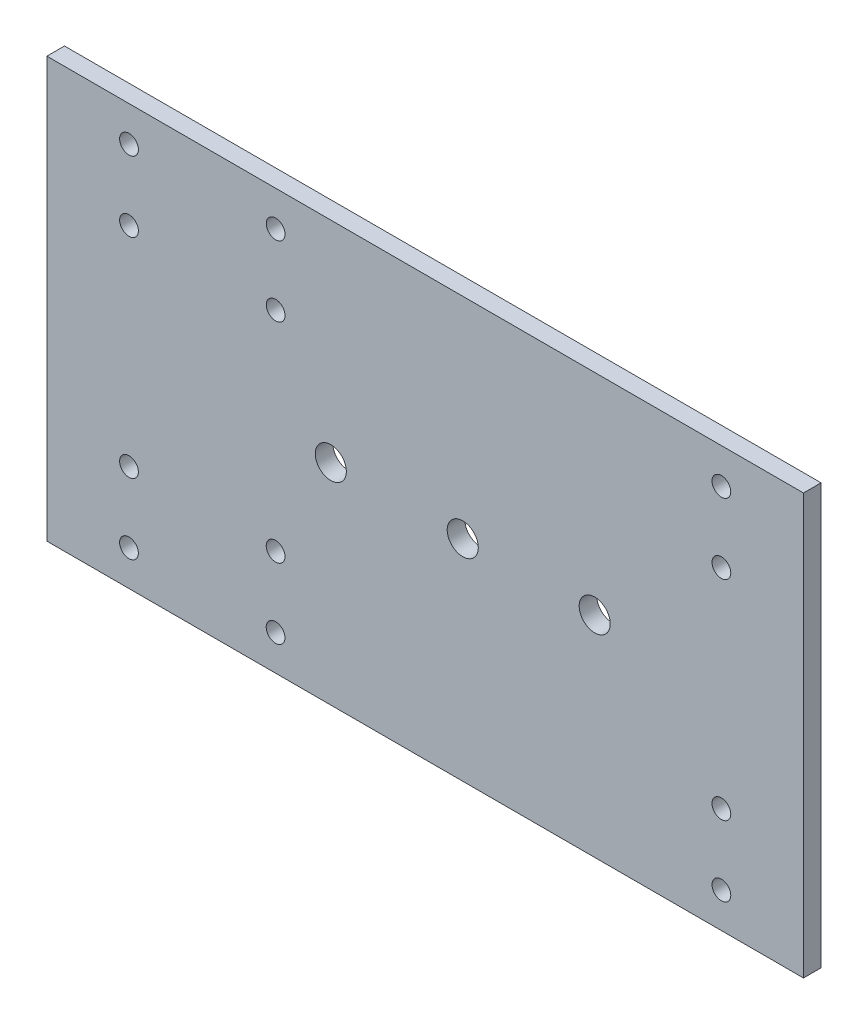
SolidWorks part; units mm, degrees
ref_plane "前视基准面" through (0, 0, 0) normal (0, 0, 1) x (1, 0, 0)
ref_plane "上视基准面" through (0, 0, 0) normal (0, 1, 0) x (1, 0, 0)
ref_plane "右视基准面" through (0, 0, 0) normal (1, 0, 0) x (0, 0, -1)
sketch "草图1" plane through (0, 0, 0) normal (0, 0, 1) x (1, 0, 0)
  line L1 (-129.0039, 24.021) -> (0, 24.021)
  line L2 (-129.0039, 24.021) -> (-129.0039, -47.6)
  line L3 (-129.0039, -47.6) -> (0, -47.6)
  line L4 (0, 24.021) -> (0, -47.6)
  circle A0 centre (-115.0045, 18.0195) radius 1.6 construction
  circle A1 centre (-115.0058, 6.0195) radius 1.6 construction
  circle A2 centre (-115.0095, -29.5805) radius 1.6 construction
  circle A3 centre (-115.0108, -41.5805) radius 1.6 construction
  circle A4 centre (-90.0095, -29.5831) radius 1.6 construction
  circle A5 centre (-90.0108, -41.5831) radius 1.6 construction
  circle A6 centre (-90.0058, 6.0169) radius 1.6 construction
  circle A7 centre (-90.0045, 18.0169) radius 1.6 construction
  circle A8 centre (-14, 18) radius 1.6 construction
  circle A9 centre (-14, 6) radius 1.6 construction
  circle A10 centre (-14, -41.6) radius 1.6 construction
  circle A11 centre (-14, -29.6) radius 1.6 construction
  circle A12 centre (-14, -29.6) radius 1.6
  circle A13 centre (-14, -41.6) radius 1.6
  circle A14 centre (-14, 6) radius 1.6
  circle A15 centre (-14, 18) radius 1.6
  circle A16 centre (-90.0045, 18.0169) radius 1.6
  circle A17 centre (-90.0058, 6.0169) radius 1.6
  circle A18 centre (-90.0108, -41.5831) radius 1.6
  circle A19 centre (-90.0095, -29.5831) radius 1.6
  circle A20 centre (-115.0108, -41.5805) radius 1.6
  circle A21 centre (-115.0095, -29.5805) radius 1.6
  circle A22 centre (-115.0058, 6.0195) radius 1.6
  circle A23 centre (-115.0045, 18.0195) radius 1.6
extrude "凸台-拉伸1" add sketch "草图1" along normal blind 3
sketch "草图2" plane through (0, 0, 3) normal (0, 0, 1) x (1, 0, 0)
  line L0 (0, -11.7895) -> (-58.1, -11.7895) construction
  line L1 (0, -47.6) -> (0, 24.021) construction
  circle A0 centre (-58.1, -11.7895) radius 2.65
  dimension "D1" = 5.3
  dimension "D2" = 58.1
extrude "切除-拉伸1" cut sketch "草图2" against normal blind 3
sketch "草图3" plane through (0, 0, 3) normal (0, 0, 1) x (1, 0, 0)
  circle A0 centre (-80.6, -11.7895) radius 2.65
  circle A1 centre (-35.6, -11.7895) radius 2.65
  dimension "D1" = 5.3
  dimension "D2" = 5.3
extrude "切除-拉伸2" cut sketch "草图3" against normal blind 3
